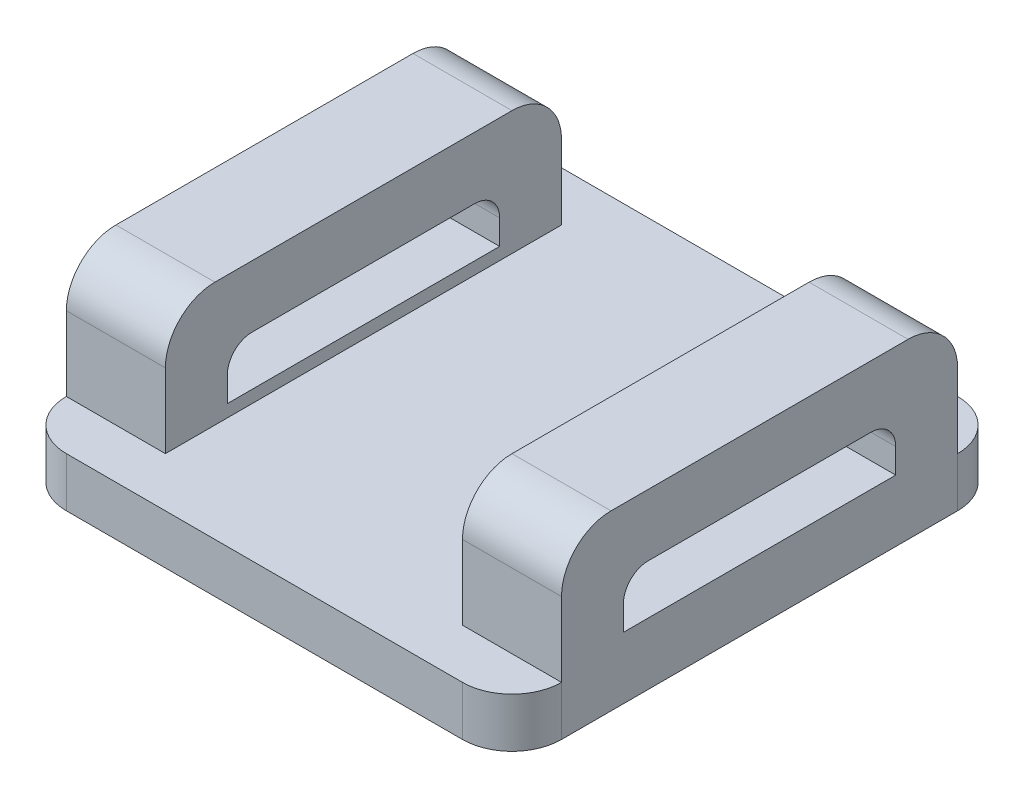
SolidWorks part; units mm, degrees
ref_plane "Alzado" through (0, 0, 0) normal (0, 0, 1) x (1, 0, 0)
ref_plane "Planta" through (0, 0, 0) normal (0, 1, 0) x (1, 0, 0)
ref_plane "Vista lateral" through (0, 0, 0) normal (1, 0, 0) x (0, 0, -1)
sketch "Croquis1" plane through (0, 0, 0) normal (0, 1, 0) x (1, 0, 0)
  line L1 (-12.5547, 11.7518) -> (7.4453, 11.7518)
  line L2 (-12.5547, 11.7518) -> (-12.5547, -8.2482)
  line L3 (-12.5547, -8.2482) -> (7.4453, -8.2482)
  line L4 (7.4453, 11.7518) -> (7.4453, -8.2482)
  dimension "D1" = 20
  dimension "D2" = 20
extrude "Saliente-Extruir1" add sketch "Croquis1" along normal blind 2
sketch "Croquis2" plane through (0, 2, 0) normal (0, 1, 0) x (1, 0, 0)
  line L0 (-12.5547, 11.7518) -> (-12.5547, -8.2482) construction
  line L1 (-12.5547, 9.7518) -> (-8.5547, 9.7518)
  line L2 (-12.5547, 9.7518) -> (-12.5547, -6.2482)
  line L3 (-12.5547, -6.2482) -> (-8.5547, -6.2482)
  line L4 (7.4453, 9.7518) -> (7.4453, -6.2482)
  line L5 (7.4453, -8.2482) -> (7.4453, 11.7518) construction
  line L6 (-12.5547, -8.2482) -> (7.4453, -8.2482) construction
  line L7 (-8.5547, 9.7518) -> (-8.5547, -6.2482)
  line L8 (3.4453, 9.7518) -> (3.4453, -6.2482)
  line L9 (3.4453, 9.7518) -> (7.4453, 9.7518)
  line L10 (3.4453, -6.2482) -> (7.4453, -6.2482)
  dimension "D1" = 16
  dimension "D2" = 2
  dimension "D3" = 4
  dimension "D4" = 4
extrude "Saliente-Extruir2" add sketch "Croquis2" along normal blind 5
sketch "Croquis3" plane through (-8.5547, 0, 0) normal (1, 0, 0) x (0, 0, -1)
  line L0 (6.2518, 4.5) -> (-2.7482, 4.5)
  line L1 (-6.2482, 2) -> (9.7518, 2) construction
  line L2 (-3.7482, 2.5) -> (7.2518, 2.5)
  line L4 (7.2518, 3.5) -> (7.2518, 2.5)
  line L5 (-3.7482, 3.5) -> (-3.7482, 2.5)
  arc A0 (6.2518, 4.5) -> (7.2518, 3.5) centre (6.2518, 3.5) cw
  arc A1 (-3.7482, 3.5) -> (-2.7482, 4.5) centre (-2.7482, 3.5) cw
  dimension "D1" = 1
  dimension "D2" = 0.5
extrude "Cortar-Extruir2" cut sketch "Croquis3" against normal blind 5
sketch "Croquis4" plane through (3.4453, 0, 0) normal (-1, 0, 0) x (0, 0, 1)
  line L0 (2.7482, 4.5) -> (-6.2518, 4.5)
  line L1 (-7.2518, 3.5) -> (-7.2518, 2.5)
  line L2 (-7.2518, 2.5) -> (3.7482, 2.5)
  line L3 (3.7482, 3.5) -> (3.7482, 2.5)
  line L4 (-9.7518, 2) -> (6.2482, 2) construction
  arc A0 (-6.2518, 4.5) -> (-7.2518, 3.5) centre (-6.2518, 3.5) ccw
  arc A1 (3.7482, 3.5) -> (2.7482, 4.5) centre (2.7482, 3.5) ccw
  dimension "D1" = 1
  dimension "D2" = 0.5
extrude "Cortar-Extruir3" cut sketch "Croquis4" against normal blind 5
fillet "Redondeo1" radius 2 4 edges at (7.4453, 1, -11.7518) (-12.5547, 1, -11.7518) (7.4453, 1, 8.2482) (-12.5547, 1, 8.2482)
fillet "Redondeo2" radius 2 4 edges at (5.4453, 7, -9.7518) (5.4453, 7, 6.2482) (-10.5547, 7, -9.7518) (-10.5547, 7, 6.2482)
